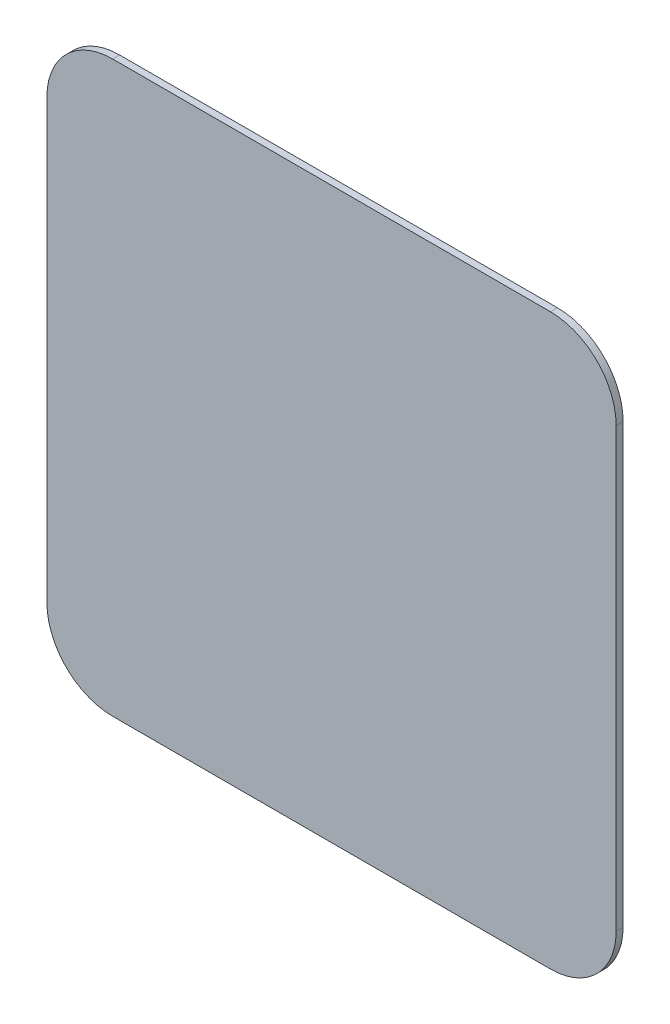
SolidWorks part; units mm, degrees
ref_plane "Front Plane" through (0, 0, 0) normal (0, 0, 1) x (1, 0, 0)
ref_plane "Top Plane" through (0, 0, 0) normal (0, 1, 0) x (1, 0, 0)
ref_plane "Right Plane" through (0, 0, 0) normal (1, 0, 0) x (0, 0, -1)
sketch "Sketch1" plane through (0, 0, 0) normal (0, 0, 1) x (1, 0, 0)
  line L0 (79.7168, 314.2679) -> (-120.2832, 314.2679) construction
  line L1 (109.7168, 84.2679) -> (109.7168, 284.2679) construction
  line L2 (-120.2832, 54.2679) -> (79.7168, 54.2679) construction
  line L3 (-150.2832, 284.2679) -> (-150.2832, 84.2679) construction
  line L4 (79.7168, 314.2679) -> (-120.2832, 314.2679)
  line L5 (109.7168, 84.2679) -> (109.7168, 284.2679)
  line L6 (-120.2832, 54.2679) -> (79.7168, 54.2679)
  line L7 (-150.2832, 284.2679) -> (-150.2832, 84.2679)
  arc A0 (-120.2832, 314.2679) -> (-150.2832, 284.2679) centre (-120.2832, 284.2679) ccw construction
  arc A1 (109.7168, 284.2679) -> (79.7168, 314.2679) centre (79.7168, 284.2679) ccw construction
  arc A2 (79.7168, 54.2679) -> (109.7168, 84.2679) centre (79.7168, 84.2679) ccw construction
  arc A3 (-150.2832, 84.2679) -> (-120.2832, 54.2679) centre (-120.2832, 84.2679) ccw construction
  arc A4 (-120.2832, 314.2679) -> (-150.2832, 284.2679) centre (-120.2832, 284.2679) ccw
  arc A5 (109.7168, 284.2679) -> (79.7168, 314.2679) centre (79.7168, 284.2679) ccw
  arc A6 (79.7168, 54.2679) -> (109.7168, 84.2679) centre (79.7168, 84.2679) ccw
  arc A7 (-150.2832, 84.2679) -> (-120.2832, 54.2679) centre (-120.2832, 84.2679) ccw
extrude "Boss-Extrude1" add sketch "Sketch1" against normal blind 3.175 contours L4 A4 L7 A7 L6 A6 L5 A5
